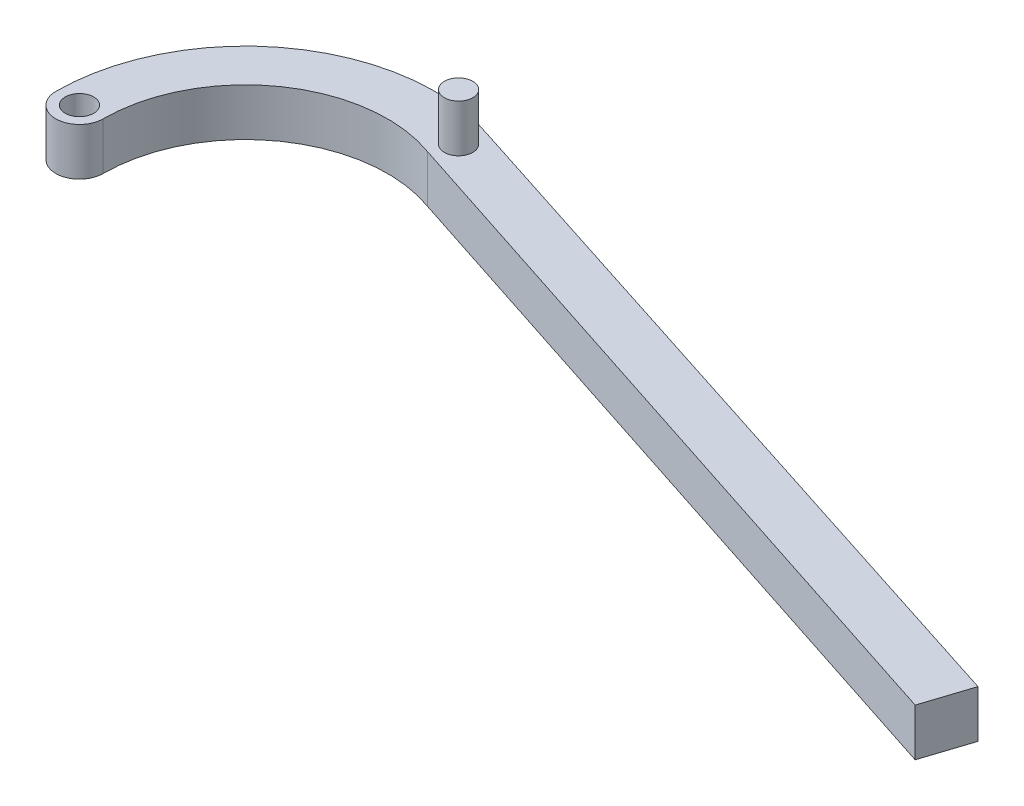
SolidWorks part; units mm, degrees
ref_plane "Front Plane" through (0, 0, 0) normal (0, 0, 1) x (1, 0, 0)
ref_plane "Top Plane" through (0, 0, 0) normal (0, 1, 0) x (1, 0, 0)
ref_plane "Right Plane" through (0, 0, 0) normal (1, 0, 0) x (0, 0, -1)
sketch "Sketch1" plane through (0, 0, 0) normal (0, 1, 0) x (1, 0, 0)
  circle A0 centre (0, 0) radius 20
  dimension "D1" = 40
extrude "Boss-Extrude1" add sketch "Sketch1" along normal blind 5
sketch "Sketch2" plane through (0, 5, 0) normal (0, 1, 0) x (1, 0, 0)
  circle A0 centre (0, 0) radius 15
  dimension "D1" = 30
extrude "Cut-Extrude1" cut sketch "Sketch2" against normal blind 5
sketch "Sketch3" plane through (0, 5, 0) normal (0, 1, 0) x (1, 0, 0)
  line L0 (6.8404, 18.7939) -> (0, 0)
  line L1 (0, 0) -> (-20, 0)
  arc A0 (-20, 0) -> (6.8404, 18.7939) centre (0, 0) ccw
  circle A1 centre (0, 0) radius 20 construction
extrude "Cut-Extrude2" cut sketch "Sketch3" against normal blind 5
sketch "Sketch10" plane through (0, 5, 0) normal (0, 1, 0) x (1, 0, 0)
  line L0 (5.1303, 14.0954) -> (81.3604, -10.7303)
  line L1 (81.3604, -10.7303) -> (82.9887, -5.7303)
  line L2 (82.9887, -5.7303) -> (6.8404, 18.7939)
  line L5 (-20, 0) -> (-15, 0)
  line L6 (5.1303, 14.0954) -> (6.8404, 18.7939)
  line L8 (5.1303, 14.0954) -> (6.8404, 18.7939)
  arc A2 (5.1303, 14.0954) -> (-15, 0) centre (0, 0) ccw
  arc A3 (6.8404, 18.7939) -> (-20, 0) centre (0, 0) ccw
  dimension "D1" = 5
  dimension "D2" = 80
  dimension "D3" = 0
extrude "Boss-Extrude6" add sketch "Sketch10" against normal blind 5
sketch "Sketch12" plane through (0, 5, 0) normal (0, 1, 0) x (1, 0, 0)
  line L0 (-15, 0) -> (-20, 0) construction
  line L1 (-20, 0) -> (-15, 0)
  arc A0 (-20, 0) -> (-15, 0) centre (-17.5, 0) ccw
extrude "Boss-Extrude7" add sketch "Sketch12" against normal blind 5
sketch "Sketch13" plane through (0, 5, 0) normal (0, 1, 0) x (1, 0, 0)
  circle A0 centre (-17.5, 0) radius 1.5
  dimension "D1" = 3
  dimension "D2" = 17.5
extrude "Cut-Extrude4" cut sketch "Sketch13" against normal blind 5
sketch "Sketch14" plane through (0, 5, 0) normal (0, 1, 0) x (1, 0, 0)
  line L0 (81.3604, -10.7303) -> (82.9887, -5.7303) construction
  line L1 (82.9887, -5.7303) -> (6.8404, 18.7939) construction
  circle A0 centre (6.0658, 16.4169) radius 1.5
  dimension "D1" = 3
  dimension "D2" = 80
  dimension "D3" = 2.5
extrude "Boss-Extrude8" add sketch "Sketch14" along normal blind 5
sketch "Sketch8" plane through (0, 5, 0) normal (0, 1, 0) x (1, 0, 0)
  circle A0 centre (-17.5, 0) radius 1.5
  dimension "D1" = 3
  dimension "D2" = 17.5
